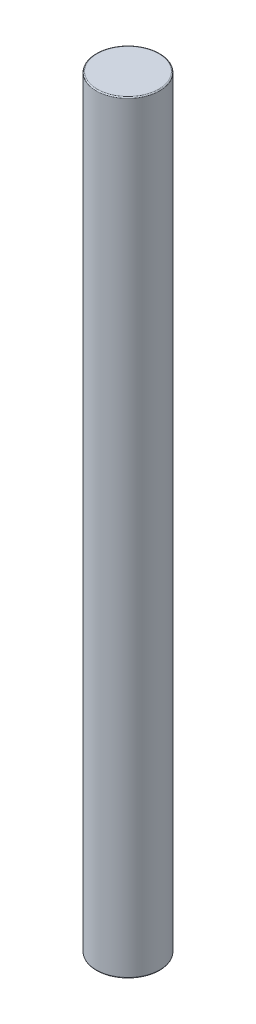
SolidWorks part; units mm, degrees
ref_plane "Front Plane" through (0, 0, 0) normal (0, 0, 1) x (1, 0, 0)
ref_plane "Top Plane" through (0, 0, 0) normal (0, 1, 0) x (1, 0, 0)
ref_plane "Right Plane" through (0, 0, 0) normal (1, 0, 0) x (0, 0, -1)
sketch "Sketch1" plane through (0, 0, 0) normal (0, 1, 0) x (1, 0, 0)
  circle A0 centre (0, 0) radius 76.2
  dimension "D1" = 152.4
extrude "Boss-Extrude1" add sketch "Sketch1" along normal blind 1828.8
fillet "Fillet1" radius 2.54 2 edges at (0, 0, 76.2) (0, 1828.8, 76.2)
